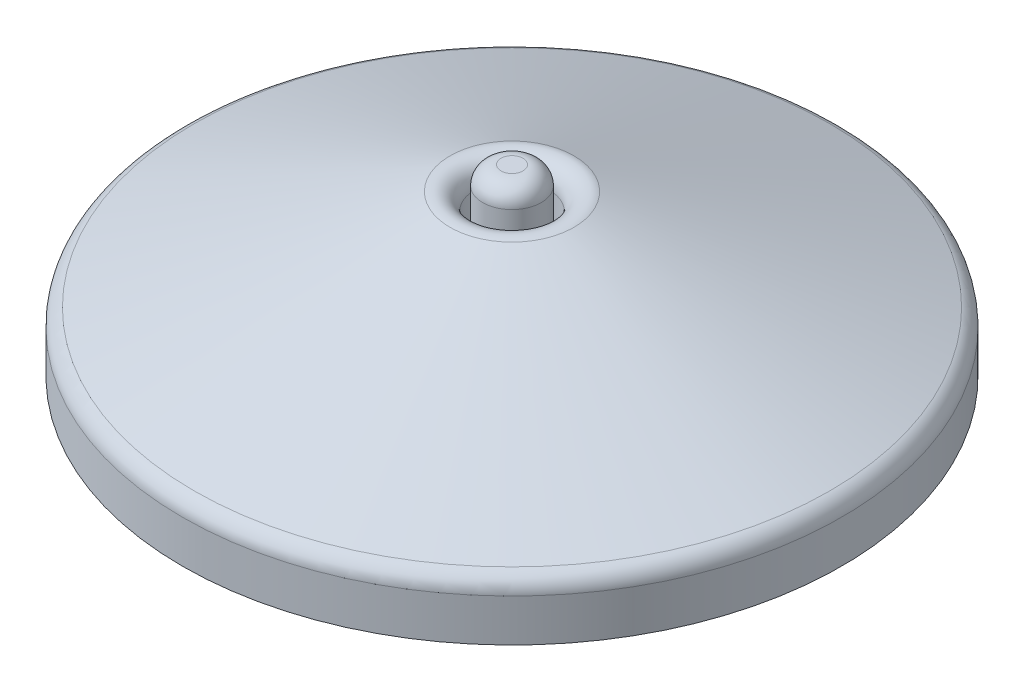
SolidWorks part; units mm, degrees
ref_plane "前视基准面" through (0, 0, 0) normal (0, 0, 1) x (1, 0, 0)
ref_plane "上视基准面" through (0, 0, 0) normal (0, 1, 0) x (1, 0, 0)
ref_plane "右视基准面" through (0, 0, 0) normal (1, 0, 0) x (0, 0, -1)
sketch "草图3" plane through (0, 0, 0) normal (0, 0, 1) x (1, 0, 0)
  line L0 (0, 0) -> (0, 35)
  line L1 (0, 35) -> (3, 35)
  line L2 (8, 30) -> (8, 0)
  line L3 (0, 0) -> (10.1, 0) construction
  line L4 (10.1, 0) -> (10.1, 23.963)
  line L5 (8, 0) -> (10.1, 0)
  line L6 (0, 0) -> (90, 0) construction
  line L7 (16.9233, 28.6187) -> (86.8233, 1.2441)
  line L8 (0, 0) -> (0, -15)
  line L9 (0, -15) -> (90, -15)
  line L10 (90, -15) -> (90, -3.4116)
  arc A0 (10.1, 23.963) -> (16.9233, 28.6187) centre (15.1, 23.963) cw
  arc A1 (3, 35) -> (8, 30) centre (3, 30) cw
  arc A2 (90, -3.4116) -> (86.8233, 1.2441) centre (85, -3.4116) ccw
  point P14 (8, 35)
  dimension "D6" = 5
  dimension "D7" = 5
  dimension "D8" = 5
  dimension "D1" = 35
  dimension "D2" = 8
  dimension "D3" = 10.1
  dimension "D4" = 90
  dimension "D5" = 15
revolve "旋转1" add sketch "草图3" angle 360 about L0
